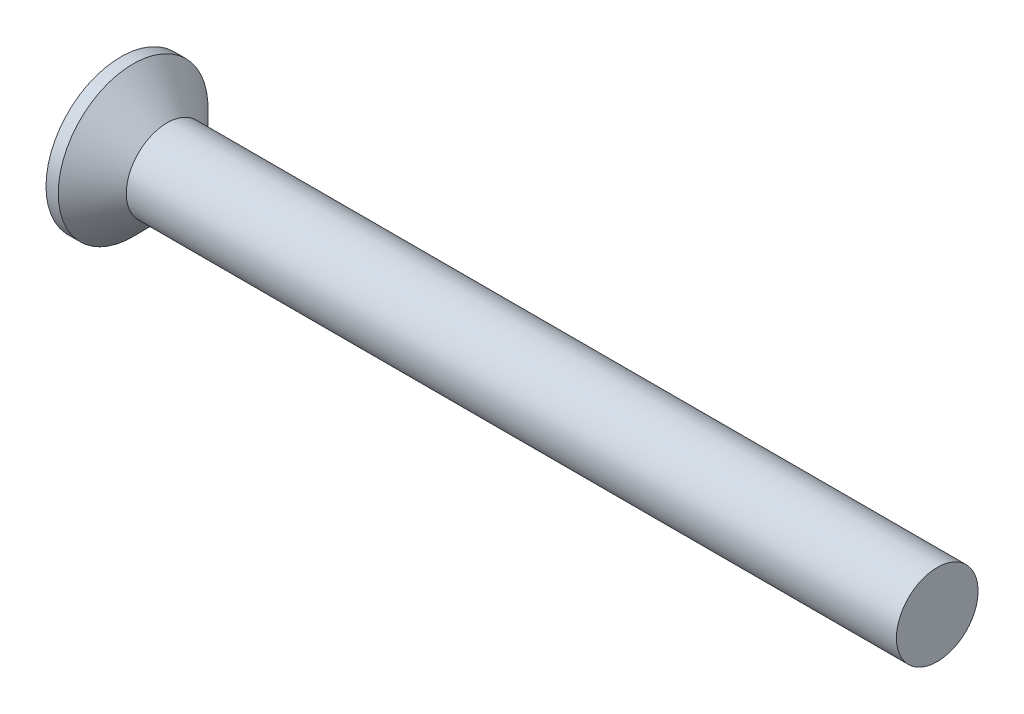
SolidWorks part; units mm, degrees
revolve "Base-Revolve" add sketch "BodySke" angle 360 about L5
sketch "BodySke" plane through (0, 0, 0) normal (0, 0, 1) x (1, 0, 0)
  line L0 (0, 0) -> (0, 2.75)
  line L1 (0, 2.75) -> (0.45, 2.75)
  line L2 (1.7, 1.5) -> (30, 1.5)
  line L3 (30, 1.5) -> (30, 0)
  line L4 (30, 0) -> (0, 0)
  line L5 (-6.35, 0) -> (82.55, 0) construction
  line L6 (1.7, -1.5) -> (30, -1.5) construction
  line L7 (0.45, -2.75) -> (1.7, -1.5) construction
  line L8 (0.45, 2.75) -> (1.7, 1.5)
  line L9 (0, -2.75) -> (0.45, -2.75) construction
  line L10 (2.2, 3.0875) -> (2.2, -6.4375) construction
  line L11 (0, 6.35) -> (0, -3.175) construction
  dimension "Diameter" = 3
  dimension "Length" = 30
  dimension "Head_ht" = 1.7
  dimension "Head_dia" = 5.5
  dimension "Head_ang" = 90
  dimension "D6" = 0.45
  dimension "Advance" = 0.5
  dimension "Thread_nom" = 30
cosmetic thread "ThreadCosmetic" [suppressed] parameters "Thread_length"=27.8, "Thread_minor"=2.439
extrude "Slot" [suppressed] cut sketch "Sketch2" against normal blind 0.9
sketch "Sketch2" plane through (0, 0, 0) normal (-1, 0, 0) x (0, 0, 1)
  line L0 (-2.75, -0.5) -> (2.75, -0.5)
  line L1 (-2.75, -0.5) -> (-2.75, 0.5)
  line L2 (2.75, 0.5) -> (-2.75, 0.5)
  line L3 (2.75, 0.5) -> (2.75, -0.5)
  dimension "Slot_width" = 1
  dimension "D1" = 0.5
  dimension "D2" = 5.5
  dimension "D3" = 2.75
ref_plane "Plane1" through (0, 0, 0) normal (0, 0, 1) x (1, 0, 0)
ref_plane "Plane2" through (0, 0, 0) normal (0, 1, 0) x (1, 0, 0)
ref_plane "Plane3" through (0, 0, 0) normal (1, 0, 0) x (0, 0, -1)
sketch "Sketch3" plane through (0, 0, 0) normal (-1, 0, 0) x (0, 0, 1)
  line L0 (-0.395, 1.55) -> (0.395, 1.55)
  line L1 (0.395, 1.55) -> (0.395, -1.55)
  line L2 (0.395, -1.55) -> (-0.395, -1.55)
  line L3 (-0.395, -1.55) -> (-0.395, 1.55)
  dimension "Cross_dia" = 3.1
  dimension "Cross_width" = 0.79
  dimension "D1" = 1.55
  dimension "D2" = 0.395
ref_plane "Plane4" through (2.08, 0, 0) normal (-1, 0, 0) x (0, 0, 1)
sketch "Sketch4" plane through (2.08, 0, 0) normal (-1, 0, 0) x (0, 0, 1)
  line L0 (-0.1975, 0.1975) -> (0.1975, 0.1975)
  line L3 (0.1975, 0.1975) -> (0.1975, -0.1975)
  line L4 (0.1975, -0.1975) -> (-0.1975, -0.1975)
  line L5 (-0.1975, -0.1975) -> (-0.1975, 0.1975)
  dimension "D2" = 0.395
  dimension "D1" = 0.395
  dimension "D3" = 0.1975
  dimension "D4" = 0.1975
loft "Cross" cut profiles "Sketch3", "Sketch4"
pattern_circular "CirPattern1" count 2 every 90 about axis through (0, 0, 0) along (1, 0, 0) of "Cross"
sketch "ThdSchSke" plane through (0, 0, 0) normal (0, 0, 1) x (1, 0, 0)
  line L0 (2.2, -1.2195) -> (2.0036, -1.5)
  line L1 (2.2, -1.2195) -> (2.3964, -1.5)
  line L2 (2.3964, -1.5) -> (2.3964, -1.875)
  line L3 (-3.175, 0) -> (5.1513, 0) construction
  line L5 (2.3964, -1.875) -> (2.0036, -1.875)
  line L6 (2.0036, -1.875) -> (2.0036, -1.5)
  line L7 (0, 2.75) -> (0, -2.75) construction
  dimension "Diameter" = 3
  dimension "Thread_minor" = 2.439
  dimension "Start" = 2.2
revolve "ThreadSchematic" [suppressed] cut sketch "ThdSchSke" angle 360 about L3
pattern_linear "ThdSchPat" [suppressed]
equation "\"D1@Sketch3\" = \"Cross_dia@Sketch3\" / 2"
equation "\"D2@Sketch3\" = \"Cross_width@Sketch3\" / 2"
equation "\"D1@Sketch4\" = \"Cross_width@Sketch3\" *.5"
equation "\"D2@Sketch4\" = \"D1@Sketch4\""
equation "\"D4@Sketch4\" = \"D2@Sketch4\" / 2"
equation "\"D3@Sketch4\" = \"D1@Sketch4\" / 2"
equation "\"D1@Sketch2\" = \"Slot_width@Sketch2\" / 2"
equation "\"D2@Sketch2\" = \"Head_dia@BodySke\""
equation "\"D3@Sketch2\" = \"D2@Sketch2\" / 2"
equation "\"Thread_length@ThreadCosmetic\" = ((sgn( (\"Length@BodySke\" - \"Advance@BodySke\" - \"Head_ht@BodySke\" ) - \"Thread_nom@BodySke\" )-1)*( (\"Length@BodySke\" - \"Advance@BodySke\" - \"Head_ht@BodySke\" ) - \"Thread_nom@BodySke\" ))/-2+ \"Thread_nom@BodySke\""
equation "\"Thread_minor@ThdSchSke\" = \"Thread_minor@ThreadCosmetic\""
equation "\"Diameter@ThdSchSke\" = \"Diameter@BodySke\""
equation "\"Overcut@ThdSchSke\" = \"Diameter@BodySke\" * 1.25"
equation "\"Start@ThdSchSke\" = 0.000001 + \"Length@BodySke\" - \"Thread_length@ThreadCosmetic\"  '---Countersunk---"
equation "\"Num_threads@ThdSchPat\" = int( \"Thread_length@ThreadCosmetic\" / \"Advance@BodySke\" + 0.999 )  + 1"
equation "\"Advance@ThdSchPat\" = \"Thread_length@ThreadCosmetic\" /  (\"Num_threads@ThdSchPat\" - 1) 'relax it"
